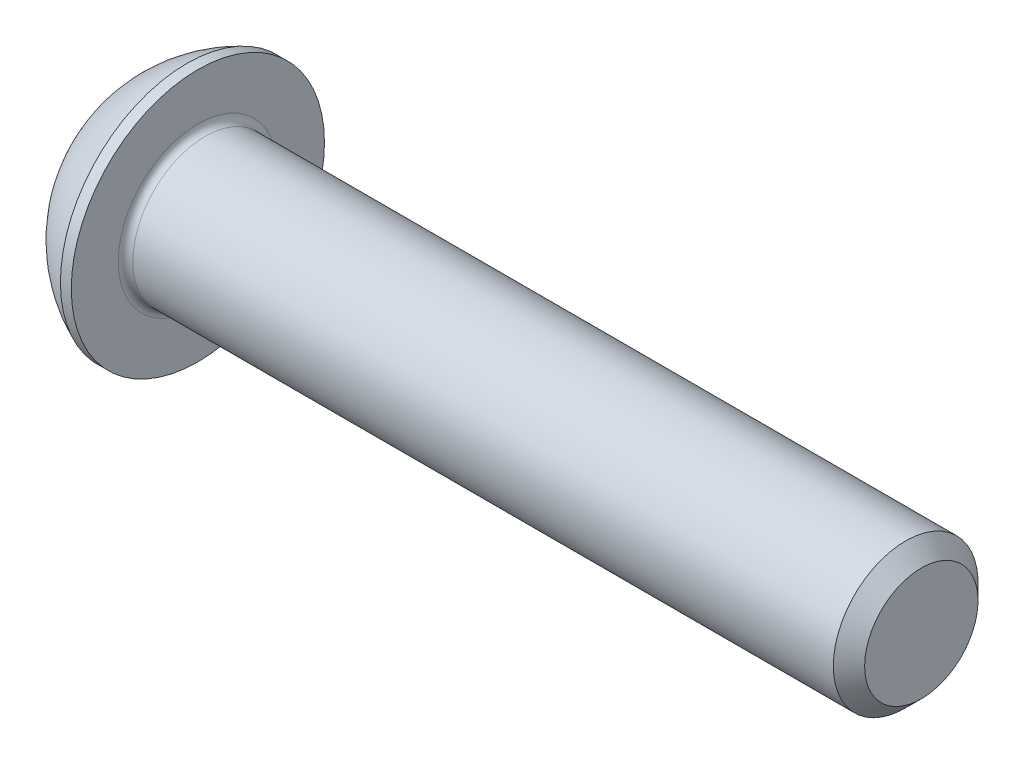
SolidWorks part; units mm, degrees
ref_plane "Plane1" through (0, 0, 0) normal (0, 0, 1) x (1, 0, 0)
ref_plane "Plane2" through (0, 0, 0) normal (0, 1, 0) x (1, 0, 0)
ref_plane "Plane3" through (0, 0, 0) normal (1, 0, 0) x (0, 0, -1)
sketch "BodySke" plane through (0, 0, 0) normal (0, 0, 1) x (1, 0, 0)
  line L0 (11.1, 0) -> (11.1, 0.7835)
  line L1 (10.8835, 1) -> (1.1, 1)
  line L2 (1.1, 1) -> (1.1, 1.75)
  line L3 (1.1, 1.75) -> (0.95, 1.75)
  line L4 (0, 0) -> (101.6, 0) construction
  line L5 (1.1, -1.75) -> (0.95, -1.75) construction
  line L6 (55.6768, -1) -> (1.1, -1) construction
  line L7 (11.1, 0) -> (0, 0)
  line L8 (0, 0.875) -> (0, -0.875) construction
  line L9 (0, 0) -> (0, 0.875)
  line L10 (11.1, 0.7835) -> (10.8835, 1)
  line L11 (11.1, -0.7835) -> (10.8835, -1) construction
  line L12 (1.5, 9.525) -> (1.5, -1) construction
  line L13 (1.1, 9.525) -> (1.1, -1) construction
  arc A1 (0, 0.875) -> (0.95, 1.75) centre (1.6839, 0) cw
  dimension "Diameter" = 2
  dimension "Length" = 10
  dimension "Head_dia" = 3.5
  dimension "D1" = 1.75
  dimension "Head_ht" = 1.1
  dimension "Head_side_ht" = 0.15
  dimension "Minor_dia" = 1.567
  dimension "Body_ch_ang" = 45
  dimension "Advance" = 0.4
  dimension "Thread_nom" = 10
revolve "BaseBody" add sketch "BodySke" angle 360 about L4
cosmetic thread "ThreadCosmetic" [suppressed] parameters "Thread_length"=9.2, "Thread_minor"=1.567
fillet "Fillet1" radius 0.1 1 edges at (1.1, 0, 1)
sketch "Sketch2" plane through (0, 0, 0) normal (0, 0, 1) x (1, 0, 0)
  line L0 (0, 0.715) -> (0.6, 0.715)
  line L1 (0.6, 0.715) -> (1.0128, 0)
  line L3 (1.0128, 0) -> (0, 0)
  line L4 (0, 0) -> (0, 0.715)
  line L5 (0, -0.715) -> (0.6, -0.715) construction
  line L6 (0, 0) -> (47.625, 0) construction
  dimension "D2" = 60
  dimension "PreBroach_depth" = 0.6
  dimension "PreBroach_dia" = 1.43
revolve "PreBroach" cut sketch "Sketch2" angle 360 about L6
sketch "Sketch3" plane through (0, 0, 0) normal (1, 0, 0) x (0, 0, -1)
  line L0 (-0.65, -0.3753) -> (-0.65, 0.3753)
  line L1 (-0.65, 0.3753) -> (0, 0.7506)
  line L2 (0, 0.7506) -> (0.65, 0.3753)
  line L3 (0.65, 0.3753) -> (0.65, -0.3753)
  line L4 (0.65, -0.3753) -> (0, -0.7506)
  line L5 (0, -0.7506) -> (-0.65, -0.3753)
  dimension "Hex_size" = 1.3
  dimension "D3" = 1.3
  dimension "D1" = 0.65
  dimension "D2" = 0.65
extrude "Hex" cut sketch "Sketch3" along normal blind 0.6
sketch "ThdSchSke" plane through (0, 0, 0) normal (0, 0, 1) x (1, 0, 0)
  line L0 (1.9, -0.7835) -> (1.7484, -1)
  line L1 (1.9, -0.7835) -> (2.0516, -1)
  line L2 (2.0516, -1) -> (2.0516, -1.25)
  line L3 (-3.175, 0) -> (5.1513, 0) construction
  line L5 (2.0516, -1.25) -> (1.7484, -1.25)
  line L6 (1.7484, -1.25) -> (1.7484, -1)
  dimension "Diameter" = 2
  dimension "Thread_minor" = 1.567
  dimension "SideAngle" = 55
  dimension "VeeAngle" = 70
  dimension "Overcut" = 2.5
  dimension "Start" = 1.9
revolve "ThreadSchematic" [suppressed] cut sketch "ThdSchSke" angle 360 about L3
pattern_linear "ThdSchPat" [suppressed]
equation "\"D1@BodySke\" = \"Head_dia@BodySke\" * .5"
equation "\"Thread_minor@ThreadCosmetic\" = \"Minor_dia@BodySke\""
equation "\"D1@Sketch3\" = \"Hex_size@Sketch3\" / 2"
equation "\"D2@Sketch3\" = \"D1@Sketch3\""
equation "\"D3@Sketch3\" = \"Hex_size@Sketch3\""
equation "\"Thread_length@ThreadCosmetic\" = ((sgn( (\"Length@BodySke\" - \"Advance@BodySke\" * 2.0) - \"Thread_nom@BodySke\" )-1)*( (\"Length@BodySke\" - \"Advance@BodySke\" * 2.0) - \"Thread_nom@BodySke\" ))/-2+ \"Thread_nom@BodySke\""
equation "\"Thread_minor@ThdSchSke\" = \"Minor_dia@BodySke\""
equation "\"Diameter@ThdSchSke\" = \"Diameter@BodySke\""
equation "\"Overcut@ThdSchSke\" = \"Diameter@BodySke\" * 1.25"
equation "\"Start@ThdSchSke\" = \"Head_ht@BodySke\" + \"Length@BodySke\" - \"Thread_length@ThreadCosmetic\"  '---Non-countersunk---"
equation "\"Num_threads@ThdSchPat\" = int( \"Thread_length@ThreadCosmetic\" / \"Advance@BodySke\" + 0.999 )  + 1"
equation "\"Advance@ThdSchPat\" = \"Thread_length@ThreadCosmetic\" /  (\"Num_threads@ThdSchPat\" - 1) 'relax it"
equation "\"Num_threads@ThdSchPat\" = \"Num_threads@ThdSchPat\" - sgn( \"Num_threads@ThdSchPat\" - 1) '---chamfered tips only---"
